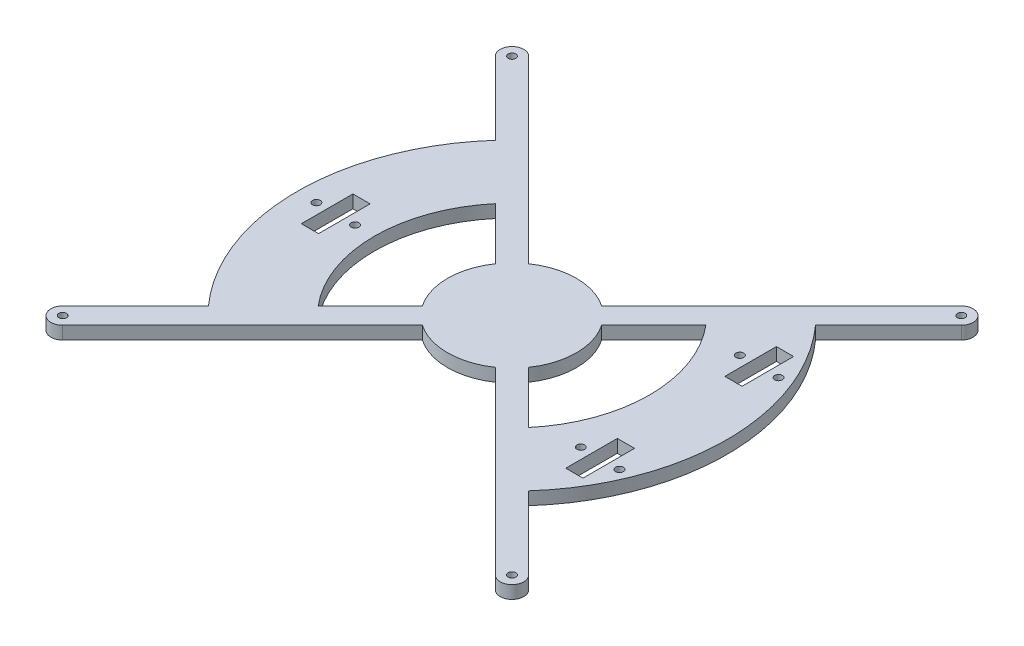
SolidWorks part; units mm, degrees
ref_plane "Front Plane" through (0, 0, 0) normal (0, 0, 1) x (1, 0, 0)
ref_plane "Top Plane" through (0, 0, 0) normal (0, 1, 0) x (1, 0, 0)
ref_plane "Right Plane" through (0, 0, 0) normal (1, 0, 0) x (0, 0, -1)
sketch "Sketch1" plane through (0, 0, 0) normal (0, 1, 0) x (1, 0, 0)
  line L0 (-110, -110) -> (110, 110) construction
  line L1 (-110, 110) -> (110, 110)
  line L2 (-110, 110) -> (-110, -110)
  line L3 (-110, -110) -> (110, -110)
  line L4 (110, 110) -> (110, -110)
  line L5 (-82, 110) -> (-82, -110) construction
  line L6 (78, 25) -> (78, -25) construction
  line L7 (0, 110) -> (0, -110) construction
  line L8 (-78, 0) -> (-73, 0) construction
  line L9 (0, 0) -> (73, 0) construction
  line L10 (-73, 0) -> (0, 0) construction
  line L11 (-86, 12) -> (-78, 12)
  line L12 (-86, 12) -> (-86, -12)
  line L13 (-86, -12) -> (-78, -12)
  line L14 (-78, 12) -> (-78, -12)
  line L15 (73, 0) -> (78, 0) construction
  line L16 (-86, 0) -> (-91, 0) construction
  line L17 (82, 37) -> (87, 37) construction
  line L18 (74, 49) -> (82, 49)
  line L19 (74, 49) -> (74, 25)
  line L20 (74, 25) -> (82, 25)
  line L21 (82, 49) -> (82, 25)
  line L22 (74, -25) -> (82, -25)
  line L23 (74, -25) -> (74, -49)
  line L24 (74, -49) -> (82, -49)
  line L25 (82, -25) -> (82, -49)
  line L26 (74, 37) -> (69, 37) construction
  line L27 (74, -37) -> (69, -37) construction
  line L28 (82, -37) -> (87, -37) construction
  circle A0 centre (-104.5, 104.5) radius 1.8
  circle A1 centre (104.5, 104.5) radius 1.8
  circle A2 centre (104.5, -104.5) radius 1.8
  circle A3 centre (-104.5, -104.5) radius 1.8
  circle A4 centre (-73, 0) radius 1.8
  circle A5 centre (-91, 0) radius 1.8
  circle A6 centre (87, 37) radius 1.8
  circle A7 centre (69, 37) radius 1.8
  circle A8 centre (87, -37) radius 1.8
  circle A9 centre (69, -37) radius 1.8
  point P26 (-82, 12)
  dimension "D3" = 3.6
  dimension "D4" = 5.5
  dimension "D5" = 5.5
  dimension "D9" = 160
  dimension "D10" = 209
  dimension "D1" = 220
  dimension "D2" = 50
  dimension "D6" = 24
  dimension "D7" = 8
  dimension "D8" = 5
extrude "Boss-Extrude1" add sketch "Sketch1" along normal mid plane 6
sketch "Sketch2" plane through (0, -3, 0) normal (0, -1, 0) x (1, 0, 0)
  line L0 (-104.5, 104.5) -> (104.5, -104.5) construction
  line L1 (-110, 110) -> (110, 110)
  line L2 (-110, 110) -> (-110, -110)
  line L3 (-110, -110) -> (110, -110)
  line L4 (110, 110) -> (110, -110)
  line L5 (104.5, 104.5) -> (-104.5, -104.5) construction
  line L6 (-100.6109, 108.3891) -> (-108.3891, 100.6109)
  line L7 (-108.3891, 100.6109) -> (-24.7427, 16.9646)
  line L8 (-100.6109, 108.3891) -> (-16.9646, 24.7427)
  line L9 (-24.7427, 16.9646) -> (-16.9646, 24.7427)
  line L10 (-108.3891, -100.6109) -> (-100.6109, -108.3891)
  line L11 (-100.6109, -108.3891) -> (-16.9646, -24.7427)
  line L12 (-16.9646, -24.7427) -> (-24.7427, -16.9646)
  line L13 (-24.7427, -16.9646) -> (-108.3891, -100.6109)
  line L14 (-91, 0) -> (-100, 0) construction
  line L15 (-73, 0) -> (-64, 0) construction
  line L16 (100.6109, -108.3891) -> (108.3891, -100.6109)
  line L17 (108.3891, -100.6109) -> (24.7427, -16.9646)
  line L18 (24.7427, -16.9646) -> (16.9646, -24.7427)
  line L19 (16.9646, -24.7427) -> (100.6109, -108.3891)
  line L20 (100.6109, 108.3891) -> (108.3891, 100.6109)
  line L21 (108.3891, 100.6109) -> (24.7427, 16.9646)
  line L22 (24.7427, 16.9646) -> (16.9646, 24.7427)
  line L23 (16.9646, 24.7427) -> (100.6109, 108.3891)
  circle A0 centre (-104.5, 104.5) radius 5.5
  circle A1 centre (0, 0) radius 100
  circle A2 centre (0, 0) radius 64
  circle A3 centre (-104.5, -104.5) radius 5.5
  circle A4 centre (0, 0) radius 30
  circle A5 centre (104.5, 104.5) radius 5.5
  circle A6 centre (104.5, -104.5) radius 5.5
  point P22 (-104.5, 104.5)
  point P27 (-104.5, -104.5)
  point P41 (92.0467, 99.8919)
  point P44 (104.5, -104.5)
  point P49 (102.2248, 87.1894)
  point P50 (104.5, 104.5)
  point P51 (107.3653, 99.8053)
  point P52 (23.4784, 15.7002)
  line M27 (-110, 110) -> (-110, -110)
  line M28 (-110, -110) -> (110, -110)
  line M29 (110, -110) -> (110, 110)
  line M30 (110, 110) -> (-110, 110)
  dimension "D1" = 11
  dimension "D3" = 9
  dimension "D4" = 11
  dimension "D6" = 60
  dimension "D2" = 11
  dimension "D5" = 11
extrude "Cut-Extrude1" cut sketch "Sketch2" against normal blind 10 contours A3 L13 A1 L7 A0 L2 | A4 L7 A2 L13 | A4 L17 A2 L21 | A6 L4 A5 L21 A1 L17 | A0 L1 M27 | A3 M27 M28 | A6 M28 M29 | A5 L4 M30 | A4 L23 A2 L8 | A2 L23 A1 L8 | A5 L1 A0 L8 A1 L23 | A6 L19 A1 L11 A3 L3 | A2 L11 A1 L19 | A4 L11 A2 L19
